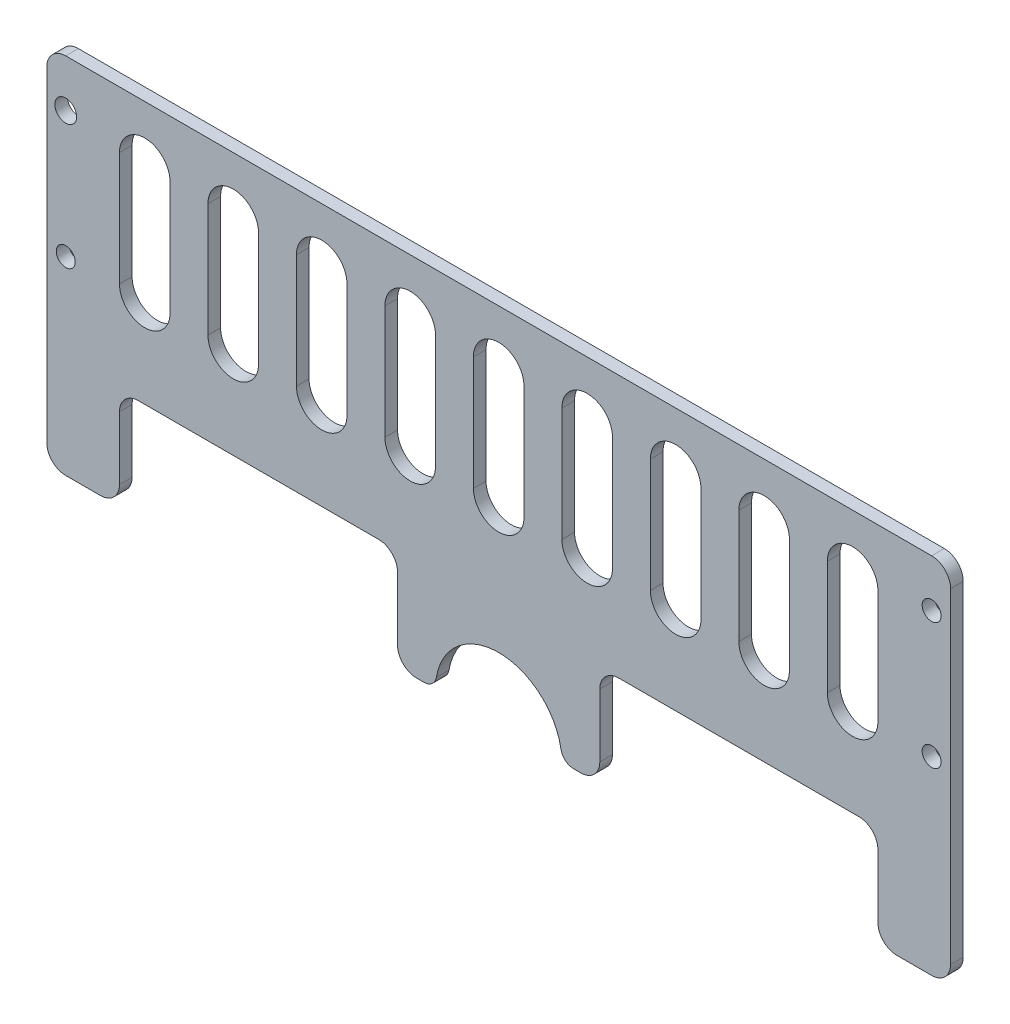
SolidWorks part; units mm, degrees
material "Thornel Mat VMA"
ref_plane "前视基准面" through (0, 0, 0) normal (0, 0, 1) x (1, 0, 0)
ref_plane "上视基准面" through (0, 0, 0) normal (0, 1, 0) x (1, 0, 0)
ref_plane "右视基准面" through (0, 0, 0) normal (1, 0, 0) x (0, 0, -1)
sketch "草图1" plane through (0, 0, 0) normal (0, 0, 1) x (1, 0, 0)
  line L1 (71.5, -28.75) -> (-71.5, -28.75)
  line L2 (71.5, -28.75) -> (71.5, 28.75)
  line L3 (71.5, 28.75) -> (-71.5, 28.75)
  line L4 (-71.5, -28.75) -> (-71.5, 28.75)
  line L5 (71.5, -28.75) -> (-71.5, 28.75) construction
  line L6 (71.5, 28.75) -> (-71.5, -28.75) construction
  point P0 (0, 0)
  dimension "D1" = 143
  dimension "D2" = 57.5
extrude "凸台-拉伸1" add sketch "草图1" along normal blind 2
sketch "草图4" plane through (0, 0, 0) normal (0, 0, -1) x (-1, 0, 0)
  line L0 (0, 28.0429) -> (0, 28.75) construction
  line L1 (-71.5, 28.75) -> (71.5, 28.75) construction
  line L2 (0, 28.75) -> (0, -28.75) construction
  line L3 (71.5, -28.75) -> (-71.5, -28.75) construction
  line L4 (-71.5, 0) -> (71.5, 0) construction
  line L5 (-71.5, -28.75) -> (-71.5, 28.75) construction
  line L6 (71.5, 28.75) -> (71.5, -28.75) construction
  line L8 (-60, -12.75) -> (60, -12.75)
  line L9 (-60, -12.75) -> (-60, -28.75)
  line L10 (-60, -28.75) -> (60, -28.75)
  line L11 (60, -12.75) -> (60, -28.75)
  line L12 (0, -28.75) -> (0, -12.75) construction
  line L13 (-60, -20.75) -> (60, -20.75) construction
  point P13 (0, -20.75)
  dimension "D1" = 16
  dimension "D2" = 120
extrude "切除-拉伸1" cut sketch "草图4" against normal blind 10
fillet "圆角1" radius 3 6 edges at (-60, -28.75, 1) (60, -28.75, 1) (71.5, -28.75, 1) (71.5, 28.75, 1) (-71.5, 28.75, 1) (-71.5, -28.75, 1)
sketch "草图5" plane through (0, 0, 2) normal (0, 0, 1) x (1, 0, 0)
  line L0 (-71.5, 10.75) -> (71.5, 10.75) construction
  line L1 (-71.5, 25.75) -> (-71.5, -25.75) construction
  line L2 (71.5, -25.75) -> (71.5, 25.75) construction
  line L3 (68.5, 28.75) -> (-68.5, 28.75) construction
  line L4 (0, 28.75) -> (0, -12.75) construction
  line L5 (60, -12.75) -> (-60, -12.75) construction
  line L6 (0, 1.75) -> (0, 19.75) construction
  line L7 (0, 19.75) -> (0, 1.75) construction
  line L8 (4, 19.75) -> (4, 1.75)
  line L9 (-4, 19.75) -> (-4, 1.75)
  line L10 (14, 1.75) -> (14, 19.75) construction
  line L11 (14, 19.75) -> (14, 1.75) construction
  line L12 (18, 19.75) -> (18, 1.75)
  line L13 (10, 19.75) -> (10, 1.75)
  line L14 (28, 1.75) -> (28, 19.75) construction
  line L15 (28, 19.75) -> (28, 1.75) construction
  line L16 (32, 19.75) -> (32, 1.75)
  line L17 (24, 19.75) -> (24, 1.75)
  line L18 (42, 1.75) -> (42, 19.75) construction
  line L19 (42, 19.75) -> (42, 1.75) construction
  line L20 (46, 19.75) -> (46, 1.75)
  line L21 (38, 19.75) -> (38, 1.75)
  line L22 (56, 1.75) -> (56, 19.75) construction
  line L23 (56, 19.75) -> (56, 1.75) construction
  line L24 (60, 19.75) -> (60, 1.75)
  line L25 (52, 19.75) -> (52, 1.75)
  line L26 (-56, 1.75) -> (-56, 19.75) construction
  line L27 (-42, 1.75) -> (-42, 19.75) construction
  line L28 (-28, 1.75) -> (-28, 19.75) construction
  line L29 (-14, 1.75) -> (-14, 19.75) construction
  line L30 (-56, 19.75) -> (-56, 1.75) construction
  line L31 (-60, 19.75) -> (-60, 1.75)
  line L32 (-52, 19.75) -> (-52, 1.75)
  line L33 (-42, 19.75) -> (-42, 1.75) construction
  line L34 (-46, 19.75) -> (-46, 1.75)
  line L35 (-38, 19.75) -> (-38, 1.75)
  line L36 (-28, 19.75) -> (-28, 1.75) construction
  line L37 (-32, 19.75) -> (-32, 1.75)
  line L38 (-24, 19.75) -> (-24, 1.75)
  line L39 (-14, 19.75) -> (-14, 1.75) construction
  line L40 (-18, 19.75) -> (-18, 1.75)
  line L41 (-10, 19.75) -> (-10, 1.75)
  arc A0 (4, 19.75) -> (-4, 19.75) centre (0, 19.75) ccw
  arc A1 (-4, 1.75) -> (4, 1.75) centre (0, 1.75) ccw
  arc A2 (18, 19.75) -> (10, 19.75) centre (14, 19.75) ccw
  arc A3 (10, 1.75) -> (18, 1.75) centre (14, 1.75) ccw
  arc A4 (32, 19.75) -> (24, 19.75) centre (28, 19.75) ccw
  arc A5 (24, 1.75) -> (32, 1.75) centre (28, 1.75) ccw
  arc A6 (46, 19.75) -> (38, 19.75) centre (42, 19.75) ccw
  arc A7 (38, 1.75) -> (46, 1.75) centre (42, 1.75) ccw
  arc A8 (60, 19.75) -> (52, 19.75) centre (56, 19.75) ccw
  arc A9 (52, 1.75) -> (60, 1.75) centre (56, 1.75) ccw
  arc A10 (-60, 19.75) -> (-52, 19.75) centre (-56, 19.75) cw
  arc A11 (-52, 1.75) -> (-60, 1.75) centre (-56, 1.75) cw
  arc A12 (-46, 19.75) -> (-38, 19.75) centre (-42, 19.75) cw
  arc A13 (-38, 1.75) -> (-46, 1.75) centre (-42, 1.75) cw
  arc A14 (-32, 19.75) -> (-24, 19.75) centre (-28, 19.75) cw
  arc A15 (-24, 1.75) -> (-32, 1.75) centre (-28, 1.75) cw
  arc A16 (-18, 19.75) -> (-10, 19.75) centre (-14, 19.75) cw
  arc A17 (-10, 1.75) -> (-18, 1.75) centre (-14, 1.75) cw
  point P12 (0, 10.75)
  point P16 (0, 10.75)
  point P21 (14, 10.75)
  point P24 (14, 10.75)
  point P29 (28, 10.75)
  point P32 (28, 10.75)
  point P37 (42, 10.75)
  point P40 (42, 10.75)
  point P45 (56, 10.75)
  point P48 (56, 10.75)
  point P60 (-56, 10.75)
  point P61 (-56, 10.75)
  point P66 (-42, 10.75)
  point P67 (-42, 10.75)
  point P72 (-28, 10.75)
  point P73 (-28, 10.75)
  point P78 (-14, 10.75)
  point P79 (-14, 10.75)
  dimension "D2" = 4
  dimension "D1" = 18
  dimension "D3" = 18
extrude "切除-拉伸2" cut sketch "草图5" against normal blind 10
sketch "草图6" plane through (0, 0, 0) normal (0, 0, -1) x (-1, 0, 0)
  line L0 (0, 28.75) -> (0, -28.75) construction
  line L1 (-68.5, 28.75) -> (68.5, 28.75) construction
  line L8 (60, -12.75) -> (-60, -12.75) construction
  line L9 (-16, -28.75) -> (16, -28.75)
  line L10 (-16, -28.75) -> (-16, -12.75)
  line L11 (-16, -12.75) -> (16, -12.75)
  line L12 (16, -28.75) -> (16, -12.75)
  line L13 (0, -12.75) -> (0, -28.75) construction
  line L14 (-16, -20.75) -> (16, -20.75) construction
  point P5 (0, -20.75)
  dimension "D1" = 16
  dimension "D2" = 32
extrude "凸台-拉伸2" add sketch "草图6" against normal blind 2
sketch "草图7" plane through (0, 0, 0) normal (0, 0, -1) x (-1, 0, 0)
  line L0 (0, 28.75) -> (0, -28.75) construction
  line L1 (-68.5, 28.75) -> (68.5, 28.75) construction
  line L2 (-16, -28.75) -> (16, -28.75) construction
  line L3 (-16, -28.75) -> (16, -28.75) construction
  line L4 (-10, -28.75) -> (10, -28.75)
  arc A0 (10, -28.75) -> (-10, -28.75) centre (0, -28.75) ccw
  arc A1 (-10, -28.75) -> (10, -28.75) centre (0, -28.75) ccw construction
  dimension "D1" = 20
extrude "切除-拉伸3" cut sketch "草图7" against normal blind 2
fillet "圆角2" radius 3 6 edges at (-60, -12.75, 1) (16, -28.75, 1) (-16, -28.75, 1) (-16, -12.75, 1) (16, -12.75, 1) (60, -12.75, 1)
fillet "圆角3" radius 2 2 edges at (10, -28.75, 1) (-10, -28.75, 1)
sketch "草图8" plane through (0, 0, 0) normal (0, 0, -1) x (-1, 0, 0)
  line L0 (-71.5, -25.75) -> (-71.5, 25.75) construction
  line L1 (-63, -28.75) -> (-68.5, -28.75) construction
  circle A0 centre (-68.5, 1.25) radius 1.5
  circle A1 centre (-68.5, 21.25) radius 1.5
  dimension "D2" = 3
  dimension "D3" = 30
  dimension "D4" = 20
  dimension "D1" = 3
extrude "切除-拉伸4" cut sketch "草图8" against normal through all
sketch "草图9" plane through (0, 0, 0) normal (0, 0, -1) x (-1, 0, 0)
  line L0 (71.5, 25.75) -> (71.5, -25.75) construction
  circle A0 centre (68.5, 1.25) radius 1.5
  point P4 (0, 0)
  dimension "D1" = 3
  dimension "D2" = 3
sketch "草图10" plane through (0, 0, 0) normal (0, 0, -1) x (-1, 0, 0)
  line L0 (71.5, 25.75) -> (71.5, -25.75) construction
  circle A0 centre (68.5, 21.25) radius 1.722
  dimension "D1" = 3
  dimension "D2" = 20
extrude "切除-拉伸5" cut sketch "草图10" against normal through all
sketch "草图12" plane through (0, 0, 0) normal (0, 0, -1) x (-1, 0, 0)
  circle A0 centre (68.5, 1.25) radius 1.5
extrude "切除-拉伸6" cut sketch "草图12" against normal through all
